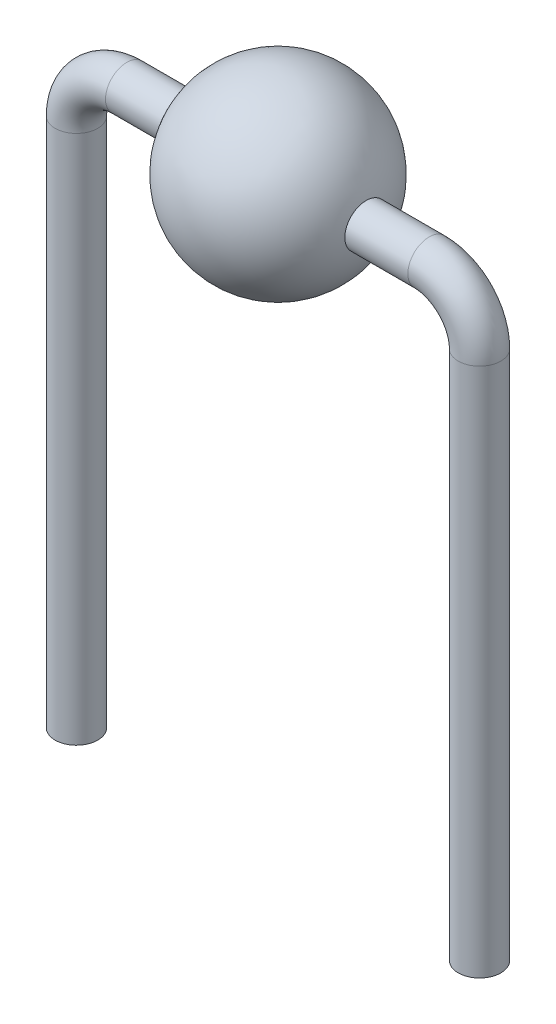
SolidWorks part; units mm, degrees
ref_plane "Спереди" through (0, 0, 0) normal (0, 0, 1) x (1, 0, 0)
ref_plane "Сверху" through (0, 0, 0) normal (0, 1, 0) x (1, 0, 0)
ref_plane "Справа" through (0, 0, 0) normal (1, 0, 0) x (0, 0, -1)
sketch "Эскиз1" plane through (0, 0, 0) normal (0, 1, 0) x (1, 0, 0)
  line L0 (-29.7512, 0) -> (31.712, 0) construction
  line L1 (-1.7496, 0.4231) -> (-1.7496, 0)
  line L2 (-1.7496, 0) -> (1.7496, 0)
  line L3 (0, 2.4294) -> (0, -0.8803) construction
  line L4 (1.7496, 0) -> (1.7496, 0.4231)
  arc A1 (-1.7496, 0.4231) -> (1.7496, 0.4231) centre (0, 0) cw
revolve "Повернуть2" add sketch "Эскиз1" angle 360 about L0
sketch "Эскиз2" plane through (0, 0, 0) normal (0, 0, 1) x (1, 0, 0)
  line L0 (0, 0) -> (-3, 0)
  line L1 (-4, -1) -> (-4, -11.5149)
  arc A1 (-3, 0) -> (-4, -1) centre (-3, -1) ccw
  point P2 (0, 0)
  point P3 (0, 0)
  dimension "D2" = 4
sketch "Эскиз3" plane through (-1.7496, 0, 0) normal (-1, 0, 0) x (0, 0, 1)
  circle A0 centre (0, 0) radius 0.4231
sweep "По траектории1" add profiles "Эскиз3" path "Эскиз2"
mirror "Зеркальное отражение1" about plane through (0, 0, 0) normal (1, 0, 0) of "По траектории1"
